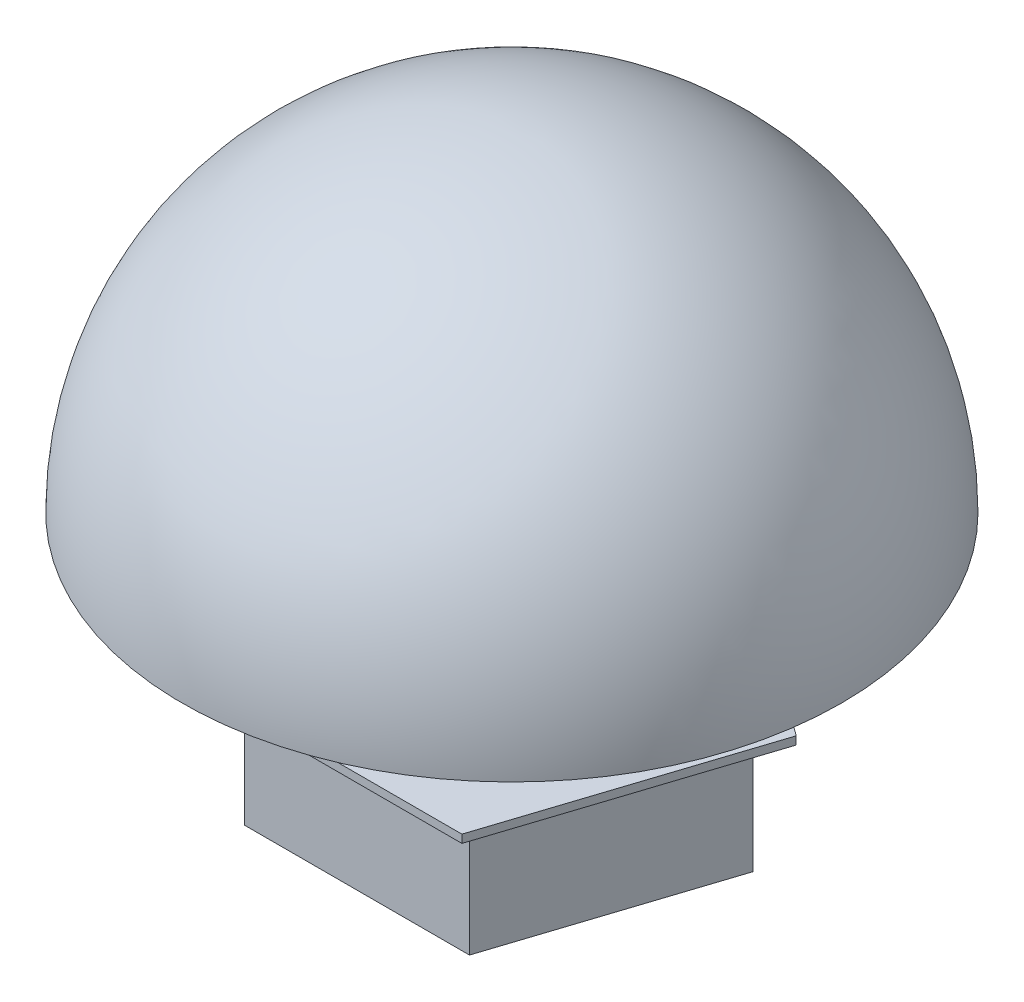
SolidWorks part; units mm, degrees
ref_plane "Front Plane" through (0, 0, 0) normal (0, 0, 1) x (1, 0, 0)
ref_plane "Top Plane" through (0, 0, 0) normal (0, 1, 0) x (1, 0, 0)
ref_plane "Right Plane" through (0, 0, 0) normal (1, 0, 0) x (0, 0, -1)
sketch "Sketch1" plane through (0, 0, 0) normal (0, 1, 0) x (1, 0, 0)
  line L1 (-22.6525, 7.3602) -> (-14, -19.2693)
  line L2 (-14, -19.2693) -> (14, -19.2693)
  line L3 (14, -19.2693) -> (22.6525, 7.3602)
  line L4 (22.6525, 7.3602) -> (0, 23.8182)
  line L5 (0, 23.8182) -> (-22.6525, 7.3602)
  line L6 (13.2735, -18.2693) -> (21.4769, 6.9783)
  line L7 (21.4769, 6.9783) -> (0, 22.5822)
  line L8 (0, 22.5822) -> (-21.4769, 6.9783)
  line L9 (-21.4769, 6.9783) -> (-13.2735, -18.2693)
  line L10 (-13.2735, -18.2693) -> (13.2735, -18.2693)
  circle A0 centre (0, 0) radius 19.2693 construction
  circle A1 centre (0, 0) radius 18.2693 construction
  point P1 (0, 0)
  dimension "D1" = 28
  dimension "D2" = 1
extrude "Boss-Extrude1" add sketch "Sketch1" along normal blind 15
sketch "Sketch2" plane through (0, 15, 0) normal (0, 1, 0) x (1, 0, 0)
  line L1 (16.5, -22.7103) -> (26.6976, 8.6746)
  line L2 (26.6976, 8.6746) -> (0, 28.0715)
  line L3 (0, 28.0715) -> (-26.6976, 8.6746)
  line L4 (-26.6976, 8.6746) -> (-16.5, -22.7103)
  line L5 (-16.5, -22.7103) -> (16.5, -22.7103)
  circle A0 centre (0, 0) radius 22.7103 construction
  point P1 (0, 0)
  dimension "D1" = 33
extrude "Boss-Extrude2" add sketch "Sketch2" along normal blind 1
sketch "Sketch3" plane through (0, 16, 0) normal (0, 1, 0) x (1, 0, 0)
  circle A0 centre (0, 0) radius 2.5
extrude "Cut-Extrude1" cut sketch "Sketch3" against normal blind 2
sketch "Sketch4" plane through (0, 16, 0) normal (0, 1, 0) x (1, 0, 0)
  line L0 (0, 8) -> (0, 19.7162) construction
  line L1 (-0.5, 19.7162) -> (0.5, 19.7162)
  line L2 (-0.5, 19.7162) -> (-0.5, 8)
  line L3 (-0.5, 8) -> (0.5, 8)
  line L4 (0.5, 19.7162) -> (0.5, 8)
  line L5 (17.3247, -9.4251) -> (7.1782, -3.567)
  line L6 (17.3247, -9.4251) -> (16.8247, -10.2911)
  line L7 (16.8247, -10.2911) -> (6.6782, -4.433)
  line L8 (7.1782, -3.567) -> (6.6782, -4.433)
  line L9 (-16.8247, -10.2911) -> (-6.6782, -4.433)
  line L10 (-16.8247, -10.2911) -> (-17.3247, -9.4251)
  line L11 (-17.3247, -9.4251) -> (-7.1782, -3.567)
  line L12 (-6.6782, -4.433) -> (-7.1782, -3.567)
  point P17 (0, 0)
  dimension "D1" = 8
  dimension "D2" = 1
  dimension "D3" = 3
extrude "Boss-Extrude4" add sketch "Sketch4" along normal blind 15
sketch "Sketch5" plane through (0, 31, 0) normal (0, 1, 0) x (1, 0, 0)
  circle A0 centre (0, 0) radius 22
sketch "Sketch6" plane through (0, 0, 0) normal (0, 0, 1) x (1, 0, 0)
  line L0 (0, 31) -> (0, 230.5153) construction
  line L1 (22, 31) -> (-22, 31) construction
  line L2 (0, 72) -> (0, 71)
  line L3 (-40, 31) -> (-41, 31)
  arc A0 (-41, 31) -> (0, 72) centre (0, 31) cw
  arc A1 (-40, 31) -> (0, 71) centre (0, 31) cw
  dimension "D1" = 1
  dimension "D2" = 40
revolve "Revolve1" add sketch "Sketch6" angle 360 about L0
sketch "Sketch7" plane through (0, 31, 0) normal (0, 1, 0) x (1, 0, 0)
  line L0 (17.3247, -9.4251) -> (7.1782, -3.567)
  line L1 (-0.5, 19.7162) -> (0.5, 19.7162)
  line L2 (-0.5, 19.7162) -> (-0.5, 8)
  line L3 (-0.5, 8) -> (0.5, 8)
  line L4 (0.5, 19.7162) -> (0.5, 8)
  line L5 (17.3247, -9.4251) -> (16.8247, -10.2911)
  line L6 (16.8247, -10.2911) -> (6.6782, -4.433)
  line L7 (7.1782, -3.567) -> (6.6782, -4.433)
  line L8 (-16.8247, -10.2911) -> (-6.6782, -4.433)
  line L9 (-16.8247, -10.2911) -> (-17.3247, -9.4251)
  line L10 (-17.3247, -9.4251) -> (-7.1782, -3.567)
  line L11 (-6.6782, -4.433) -> (-7.1782, -3.567)
  point P16 (0, 0)
  dimension "D1" = 3
extrude "Boss-Extrude6" add sketch "Sketch7" along normal up to next
